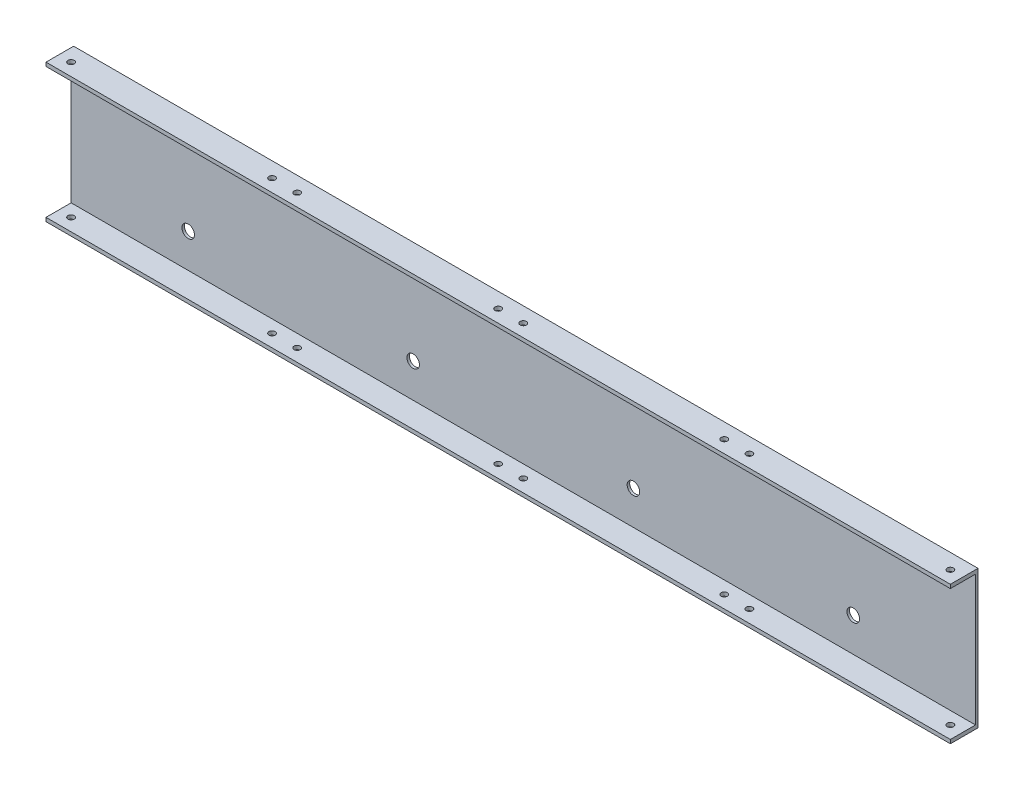
SolidWorks part; units mm, degrees
material "6063-O"
ref_plane "前视基准面" through (0, 0, 0) normal (0, 0, 1) x (1, 0, 0)
ref_plane "上视基准面" through (0, 0, 0) normal (0, 1, 0) x (1, 0, 0)
ref_plane "右视基准面" through (0, 0, 0) normal (1, 0, 0) x (0, 0, -1)
sketch "草图1" plane through (0, 0, 0) normal (0, 0, 1) x (1, 0, 0)
  line L0 (-93.2193, 74.5194) -> (626.7807, 74.5194)
  line L2 (626.7807, 74.5194) -> (626.7807, -35.4806)
  line L4 (626.7807, -35.4806) -> (-93.2193, -35.4806)
  line L10 (-93.2193, -35.4806) -> (-93.2193, 74.5194)
  circle A6 centre (0, -5.4806) radius 5
  circle A7 centre (179.095, -5.4806) radius 5
  circle A8 centre (354.4665, -5.4806) radius 5
  circle A9 centre (529.4665, -5.4806) radius 5
extrude "凸台-拉伸1" add sketch "草图1" along normal blind 2
sketch "草图2" plane through (0, 0, 2) normal (0, 0, 1) x (1, 0, 0)
  line L0 (626.7807, -35.4806) -> (626.7807, 74.5194) construction
  line L1 (-93.2193, 74.5194) -> (626.7807, 74.5194)
  line L2 (-93.2193, 74.5194) -> (-93.2193, 71.5194)
  line L3 (-93.2193, 71.5194) -> (626.7807, 71.5194)
  line L4 (626.7807, 74.5194) -> (626.7807, 71.5194)
  line L6 (-93.2193, -35.4806) -> (626.7807, -35.4806)
  line L7 (-93.2193, -35.4806) -> (-93.2193, -32.4806)
  line L8 (-93.2193, -32.4806) -> (626.7807, -32.4806)
  line L9 (626.7807, -35.4806) -> (626.7807, -32.4806)
extrude "凸台-拉伸2" add sketch "草图2" along normal blind 20
sketch "草图3" plane through (0, 74.5194, 0) normal (0, 1, 0) x (1, 0, 0)
  circle A1 centre (456.7807, -12) radius 2.5
  circle A2 centre (616.7807, -12) radius 2.5
  circle A3 centre (436.7807, -12) radius 2.5
  circle A4 centre (276.7807, -12) radius 2.5
  circle A5 centre (256.7807, -12) radius 2.5
  circle A6 centre (96.7807, -12) radius 2.5
  circle A7 centre (76.7807, -12) radius 2.5
  circle A8 centre (-83.2193, -12) radius 2.5
extrude "切除-拉伸3" cut sketch "草图3" against normal blind 114
